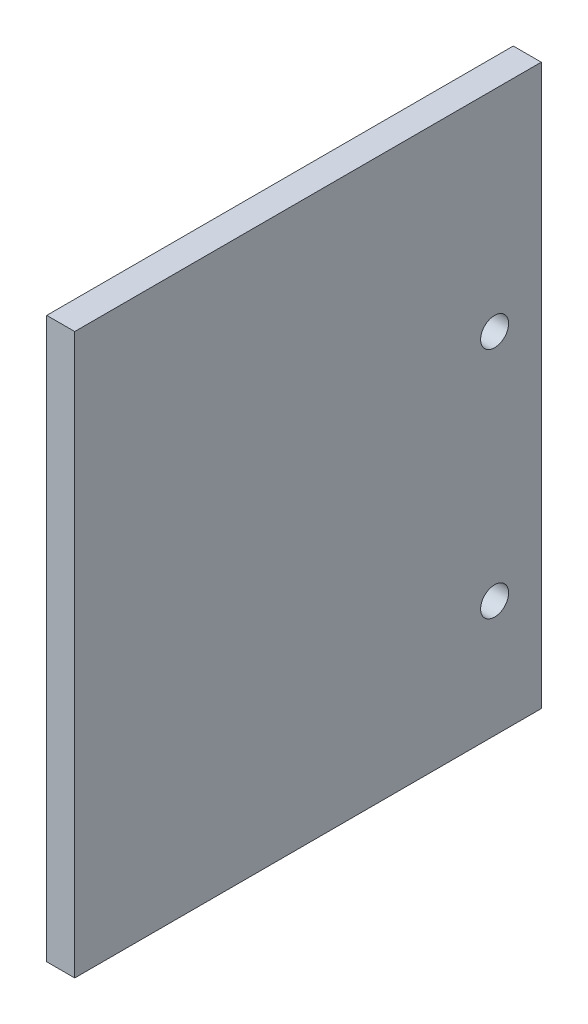
SolidWorks part; units mm, degrees
material "Perspex (TM) GS Acrylic Cast Sheet"
ref_plane "Ebene vorne" through (0, 0, 0) normal (0, 0, 1) x (1, 0, 0)
ref_plane "Ebene oben" through (0, 0, 0) normal (0, 1, 0) x (1, 0, 0)
ref_plane "Ebene rechts" through (0, 0, 0) normal (1, 0, 0) x (0, 0, -1)
sketch "Skizze1" plane through (0, 0, 0) normal (1, 0, 0) x (0, 0, -1)
  line L1 (-25, 30) -> (25, 30)
  line L2 (-25, 30) -> (-25, -30)
  line L3 (-25, -30) -> (25, -30)
  line L4 (25, 30) -> (25, -30)
  line L5 (-25, 30) -> (25, -30) construction
  line L6 (-25, -30) -> (25, 30) construction
  point P0 (0, 0)
  dimension "D1" = 50
  dimension "D2" = 60
extrude "Aufsatz-Linear austragen1" add sketch "Skizze1" along normal blind 3
sketch "Skizze2" plane through (3, 0, 0) normal (1, 0, 0) x (0, 0, -1)
  line L0 (25, 30) -> (-25, 30) construction
  line L1 (0, 30) -> (-25, 30) construction
  line L2 (0, 30) -> (0, 20) construction
  line L3 (0, 20) -> (-25, 20) construction
  line L4 (-25, 30) -> (-25, 20) construction
  line L5 (0, 30) -> (-25, 20) construction
  line L6 (0, 20) -> (-25, 30) construction
  line L7 (-25, 30) -> (-25, -30) construction
  line L8 (25, -30) -> (25, 30) construction
  line L9 (0, 20) -> (25, 20) construction
  line L10 (0, 20) -> (0, 30) construction
  line L11 (0, 30) -> (25, 30) construction
  line L12 (25, 20) -> (25, 30) construction
  line L13 (0, 20) -> (25, 30) construction
  line L14 (0, 30) -> (25, 20) construction
  line L15 (25, -30) -> (25, 30) construction
  line L17 (25, 20) -> (15, 20) construction
  line L18 (25, 20) -> (25, -5) construction
  line L19 (25, -5) -> (15, -5) construction
  line L20 (15, 20) -> (15, -5) construction
  line L21 (25, 20) -> (15, -5) construction
  line L22 (25, -5) -> (15, 20) construction
  line L23 (15, -5) -> (25, -5) construction
  line L24 (15, -5) -> (15, -30) construction
  line L25 (15, -30) -> (25, -30) construction
  line L26 (25, -5) -> (25, -30) construction
  line L27 (15, -5) -> (25, -30) construction
  line L28 (15, -30) -> (25, -5) construction
  circle A0 centre (12.5, 25) radius 1.5 construction
  circle A1 centre (-12.5, 25) radius 1.5 construction
  circle A2 centre (20, 7.5) radius 1.5
  circle A3 centre (20, -17.5) radius 1.5
  point P4 (-12.5, 25)
  point P11 (12.5, 25)
  point P24 (20, 7.5)
  point P27 (20, -17.5)
  dimension "D2" = 3
  dimension "D1" = 10
extrude "Schnitt-Linear austragen1" cut sketch "Skizze2" against normal through all
